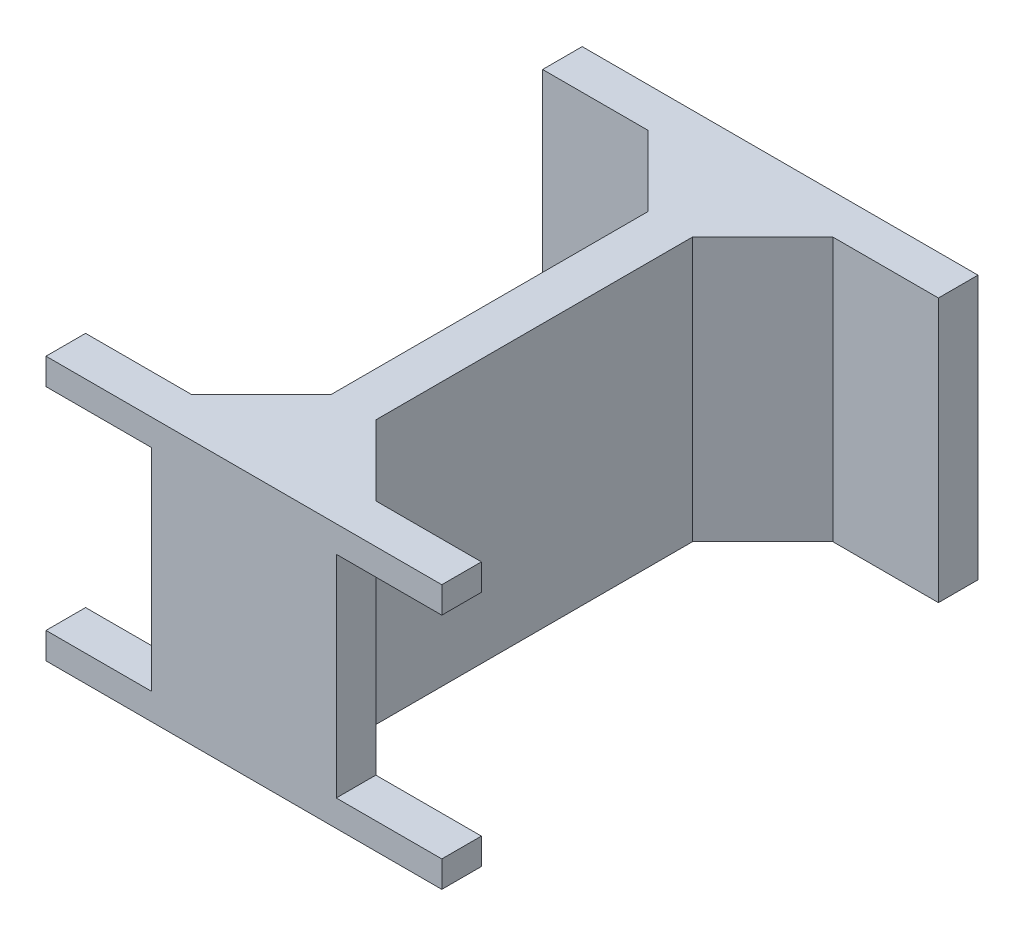
SolidWorks part; units mm, degrees
ref_plane "Front Plane" through (0, 0, 0) normal (0, 0, 1) x (1, 0, 0)
ref_plane "Top Plane" through (0, 0, 0) normal (0, 1, 0) x (1, 0, 0)
ref_plane "Right Plane" through (0, 0, 0) normal (1, 0, 0) x (0, 0, -1)
sketch "Sketch2" plane through (0, 0, 0) normal (0, 0, 1) x (1, 0, 0)
  line L1 (-40.8077, 18.1865) -> (34.1923, 18.1865)
  line L2 (-40.8077, 18.1865) -> (-40.8077, -31.8135)
  line L3 (-40.8077, -31.8135) -> (34.1923, -31.8135)
  line L4 (34.1923, 18.1865) -> (34.1923, -31.8135)
  dimension "D1" = 75
  dimension "D2" = 50
extrude "Boss-Extrude1" add sketch "Sketch2" along normal blind 101.6
sketch "Sketch3" plane through (0, 18.1865, 0) normal (0, 1, 0) x (1, 0, 0)
  line L0 (-40.8077, -7.5) -> (-20.8077, -7.5)
  line L1 (-40.8077, -101.6) -> (-40.8077, 0) construction
  line L2 (-20.8077, -7.5) -> (-7.5077, -20.8)
  line L3 (-7.5077, -20.8) -> (-7.5077, -80.8)
  line L4 (-7.5077, -80.8) -> (-20.8077, -94.1)
  line L5 (-20.8077, -94.1) -> (-40.8077, -94.1)
  line L6 (-40.8077, -94.1) -> (-40.8077, -7.5)
  line L7 (34.1923, -101.6) -> (-40.8077, -101.6) construction
  line L8 (34.1923, 0) -> (-40.8077, 0) construction
  point P4 (-23.7282, -93.1935)
  point P9 (-17.1929, -85.3771)
  point P10 (-29.3077, -14.7307)
  point P11 (-3.1459, -76.4641)
  point P12 (-16.0032, -11.097)
  dimension "D1" = 7.5
  dimension "D2" = 7.5
  dimension "D3" = 20
  dimension "D4" = 20
  dimension "D5" = 135
  dimension "D6" = 60
extrude "Cut-Extrude1" cut sketch "Sketch3" against normal blind 101.6
sketch "Sketch4" plane through (0, 18.1865, 0) normal (0, 1, 0) x (1, 0, 0)
  line L0 (34.1923, -94.1) -> (14.1923, -94.1)
  line L1 (34.1923, -101.6) -> (34.1923, 0) construction
  line L2 (14.1923, -94.1) -> (0.8923, -80.8)
  line L3 (0.8923, -80.8) -> (0.8923, -20.8)
  line L4 (0.8923, -20.8) -> (14.1923, -7.5)
  line L5 (14.1923, -7.5) -> (34.1923, -7.5)
  line L6 (34.1923, -7.5) -> (34.1923, -94.1)
  line L7 (34.1923, -101.6) -> (-40.8077, -101.6) construction
  line L8 (34.1923, 0) -> (-40.8077, 0) construction
  dimension "D1" = 7.5
  dimension "D2" = 7.5
  dimension "D3" = 20
  dimension "D4" = 20
  dimension "D5" = 135
  dimension "D6" = 135
  dimension "D7" = 60
extrude "Cut-Extrude2" cut sketch "Sketch4" against normal blind 101.6
sketch "Sketch5" plane through (0, 0, 101.6) normal (0, 0, 1) x (1, 0, 0)
  line L0 (34.1923, -31.8135) -> (34.1923, 18.1865) construction
  line L1 (34.1923, -26.8135) -> (14.1923, -26.8135)
  line L2 (34.1923, -26.8135) -> (34.1923, 13.1865)
  line L3 (34.1923, 13.1865) -> (14.1923, 13.1865)
  line L4 (14.1923, -26.8135) -> (14.1923, 13.1865)
  line L5 (-40.8077, -31.8135) -> (34.1923, -31.8135) construction
  dimension "D1" = 5
  dimension "D2" = 40
  dimension "D3" = 20
extrude "Cut-Extrude3" cut sketch "Sketch5" against normal blind 10
sketch "Sketch6" plane through (0, 0, 101.6) normal (0, 0, 1) x (1, 0, 0)
  line L0 (-40.8077, 18.1865) -> (-40.8077, -31.8135) construction
  line L1 (-40.8077, 13.1865) -> (-20.8077, 13.1865)
  line L2 (-40.8077, 13.1865) -> (-40.8077, -26.8135)
  line L3 (-40.8077, -26.8135) -> (-20.8077, -26.8135)
  line L4 (-20.8077, 13.1865) -> (-20.8077, -26.8135)
  line L5 (34.1923, 18.1865) -> (-40.8077, 18.1865) construction
  dimension "D1" = 20
  dimension "D2" = 40
  dimension "D3" = 5
extrude "Cut-Extrude4" cut sketch "Sketch6" against normal blind 10
